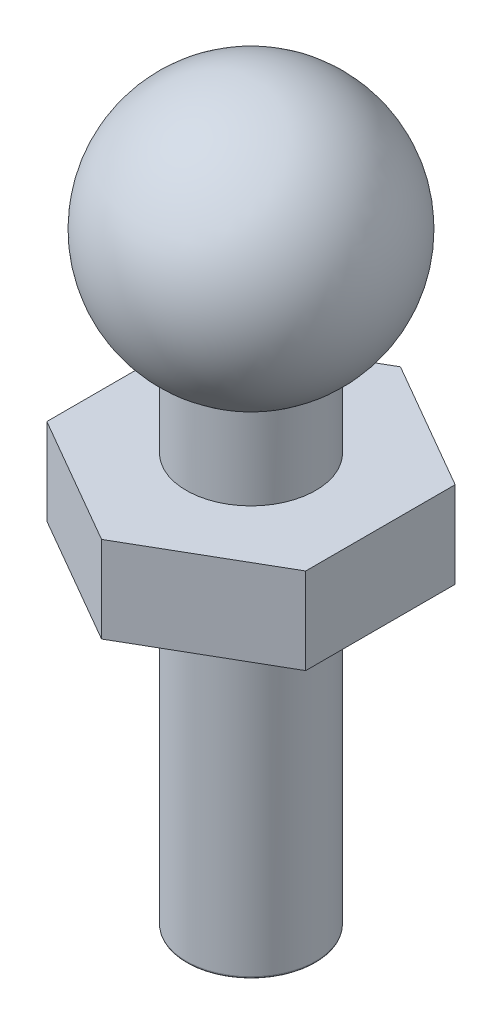
SolidWorks part; units mm, degrees
ref_plane "Front Plane" through (0, 0, 0) normal (0, 0, 1) x (1, 0, 0)
ref_plane "Top Plane" through (0, 0, 0) normal (0, 1, 0) x (1, 0, 0)
ref_plane "Right Plane" through (0, 0, 0) normal (1, 0, 0) x (0, 0, -1)
sketch "Sketch1" plane through (0, 0, 0) normal (0, 0, 1) x (1, 0, 0)
  line L0 (0, 11) -> (0, 0)
  line L1 (0, 0) -> (1.5, 0)
  line L2 (1.5, 0) -> (1.5, 11.4019)
  line L3 (0, 11) -> (0, 17)
  circle A0 centre (0, 14) radius 3 construction
  arc A2 (1.5, 11.4019) -> (0, 17) centre (0, 14) ccw
  dimension "D1" = 6
  dimension "D2" = 1.5
  dimension "D3" = 11
revolve "Revolve1" add sketch "Sketch1" angle 360 about L0
sketch "Sketch2" plane through (0, 0, 0) normal (0, 0, 1) x (1, 0, 0)
  line L0 (-4.5323, 7.5) -> (6.8824, 7.5)
  dimension "D1" = 7.5
split line "Split Line1"
fillet "Fillet1" radius 0.05 1 edges at (-1.5, 0, 0)
ref_plane "Plane1" through (0, 7.5, 0) normal (0, -1, 0) x (-1, 0, 0)
sketch "Sketch3" plane through (0, 7.5, 0) normal (0, -1, 0) x (-1, 0, 0)
  line L1 (0, 3.4641) -> (-3, 1.7321)
  line L2 (-3, 1.7321) -> (-3, -1.7321)
  line L3 (-3, -1.7321) -> (0, -3.4641)
  line L4 (0, -3.4641) -> (3, -1.7321)
  line L5 (3, -1.7321) -> (3, 1.7321)
  line L6 (3, 1.7321) -> (0, 3.4641)
  circle A0 centre (0, 0) radius 1.4917
  circle A1 centre (0, 0) radius 3 construction
  dimension "D1" = 6
extrude "Boss-Extrude1" add sketch "Sketch3" against normal blind 2
